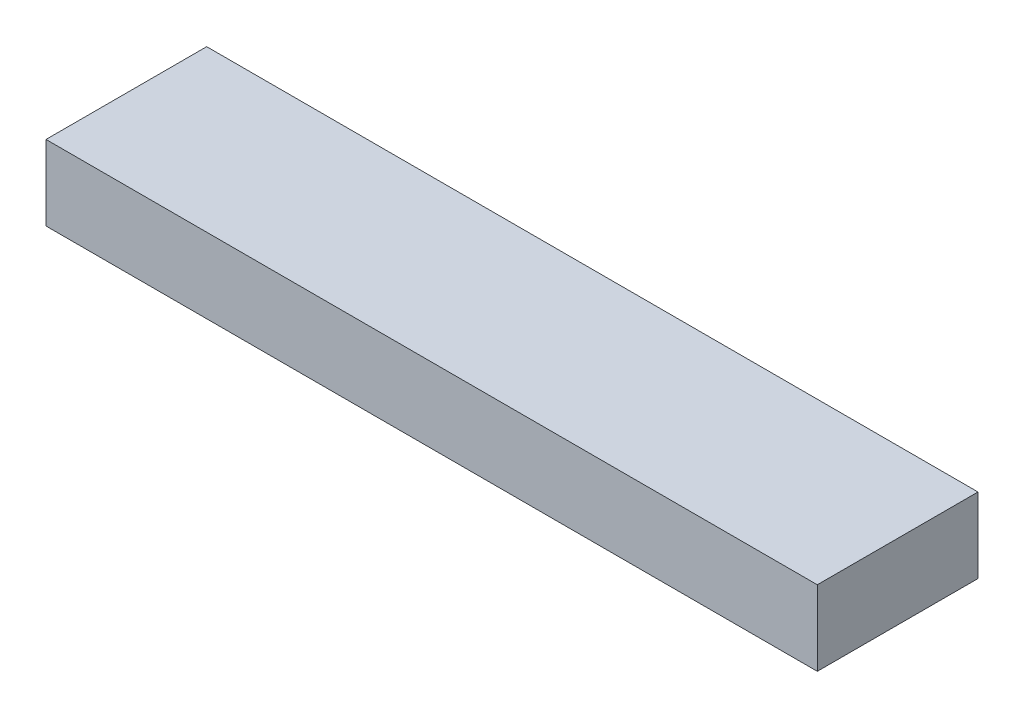
SolidWorks part; units mm, degrees
material "Pino"
ref_plane "Alzado" through (0, 0, 0) normal (0, 0, 1) x (1, 0, 0)
ref_plane "Planta" through (0, 0, 0) normal (0, 1, 0) x (1, 0, 0)
ref_plane "Vista lateral" through (0, 0, 0) normal (1, 0, 0) x (0, 0, -1)
sketch "Croquis2" plane through (0, 0, 0) normal (0, 1, 0) x (1, 0, 0)
  line L1 (-180, -37.5) -> (180, -37.5)
  line L2 (-180, -37.5) -> (-180, 37.5)
  line L3 (-180, 37.5) -> (180, 37.5)
  line L4 (180, -37.5) -> (180, 37.5)
  line L5 (-180, -37.5) -> (180, 37.5) construction
  line L6 (-180, 37.5) -> (180, -37.5) construction
  point P0 (0, 0)
  dimension "D1" = 360
  dimension "D2" = 75
extrude "Saliente-Extruir1" add sketch "Croquis2" along normal blind 35
